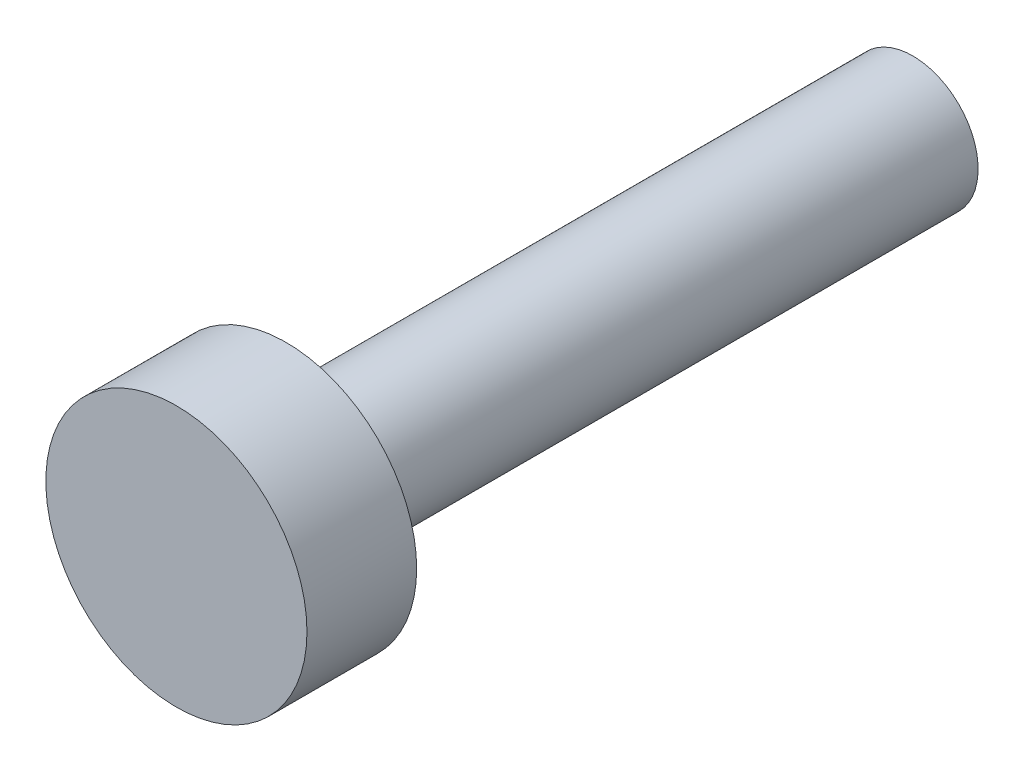
SolidWorks part; units mm, degrees
ref_plane "Plan de face" through (0, 0, 0) normal (0, 0, 1) x (1, 0, 0)
ref_plane "Plan de dessus" through (0, 0, 0) normal (0, 1, 0) x (1, 0, 0)
ref_plane "Plan de droite" through (0, 0, 0) normal (1, 0, 0) x (0, 0, -1)
sketch "Esquisse1" plane through (0, 0, 0) normal (0, 0, 1) x (1, 0, 0)
  circle A0 centre (0, 0) radius 2.5
  dimension "D1" = 5
extrude "Boss.-Extru.1" add sketch "Esquisse1" along normal blind 2.1
sketch "Esquisse2" plane through (0, 0, 0) normal (0, 0, -1) x (-1, 0, 0)
  circle A0 centre (0, 0) radius 1.25
  dimension "D1" = 2.5
extrude "Boss.-Extru.2" add sketch "Esquisse2" along normal blind 12
